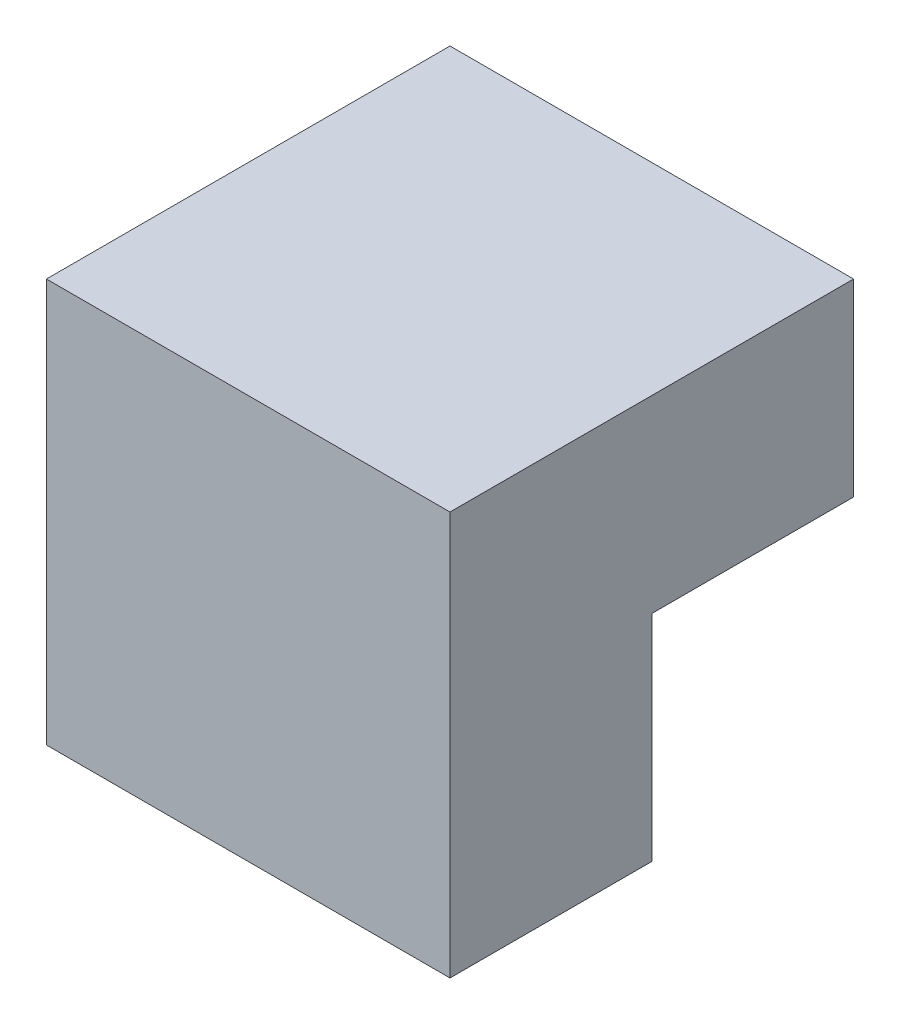
SolidWorks part; units mm, degrees
ref_plane "前视基准面" through (0, 0, 0) normal (0, 0, 1) x (1, 0, 0)
ref_plane "上视基准面" through (0, 0, 0) normal (0, 1, 0) x (1, 0, 0)
ref_plane "右视基准面" through (0, 0, 0) normal (1, 0, 0) x (0, 0, -1)
sketch "草图1" plane through (0, 0, 0) normal (0, 0, 1) x (1, 0, 0)
  line L1 (-7.3066, 6.5124) -> (12.6934, 6.5124)
  line L2 (-7.3066, 6.5124) -> (-7.3066, -13.4876)
  line L3 (-7.3066, -13.4876) -> (12.6934, -13.4876)
  line L4 (12.6934, 6.5124) -> (12.6934, -13.4876)
  dimension "D1" = 20
  dimension "D2" = 20
extrude "凸台-拉伸1" add sketch "草图1" along normal blind 20
sketch "草图2" plane through (0, 0, 0) normal (0, 0, 1) x (1, 0, 0)
  circle A0 centre (3.9824, -52.081) radius 50
  dimension "D1" = 100
extrude "切除-拉伸1" cut sketch "草图2" along normal blind 10
